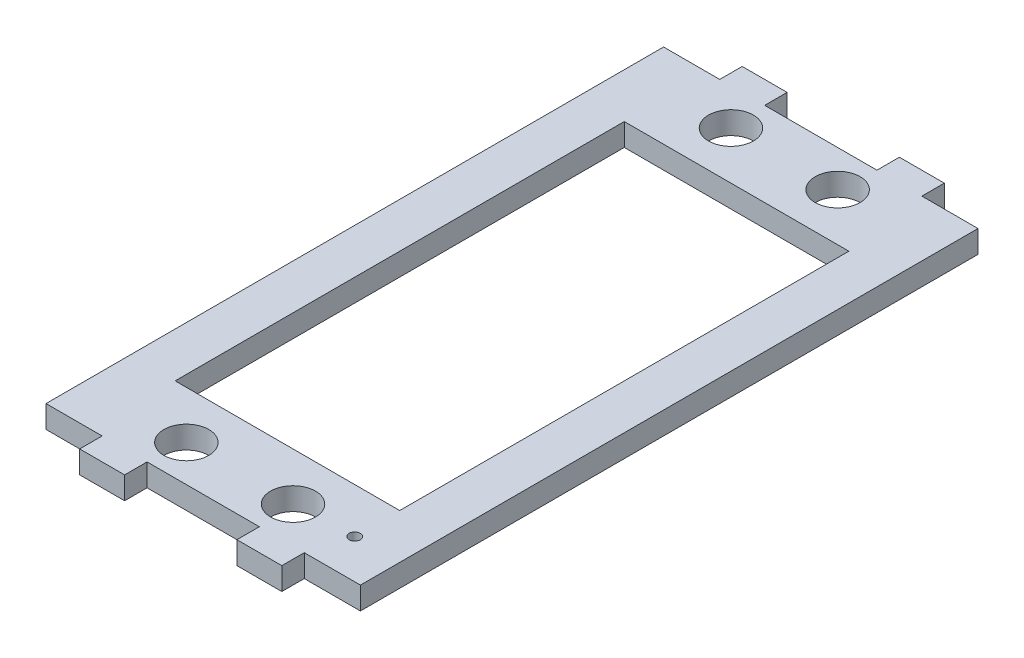
SolidWorks part; units mm, degrees
ref_plane "Front Plane" through (0, 0, 0) normal (0, 0, 1) x (1, 0, 0)
ref_plane "Top Plane" through (0, 0, 0) normal (0, 1, 0) x (1, 0, 0)
ref_plane "Right Plane" through (0, 0, 0) normal (1, 0, 0) x (0, 0, -1)
sketch "Sketch1" plane through (0, 0, 0) normal (0, 1, 0) x (1, 0, 0)
  line L0 (0, 27.2) -> (0, -27.2) construction
  line L1 (-10, -20) -> (10, -20)
  line L2 (-10, -20) -> (-10, 20)
  line L3 (-10, 20) -> (10, 20)
  line L4 (10, -20) -> (10, 20)
  line L5 (-10, -20) -> (10, 20) construction
  line L6 (-10, 20) -> (10, -20) construction
  line L7 (-14, -27.5) -> (-9, -27.5)
  line L8 (-14, -14.5) -> (-14, 14.5)
  line L9 (-14, 27.5) -> (-9, 27.5)
  line L10 (14, -27.5) -> (14, 27.5)
  line L11 (-14, -27.5) -> (14, 27.5) construction
  line L12 (-14, 27.5) -> (14, -27.5) construction
  line L18 (5, 27.5) -> (5, 29.5)
  line L19 (5, 29.5) -> (9, 29.5)
  line L20 (9, 27.5) -> (9, 29.5)
  line L21 (-14, 0) -> (14, 0) construction
  line L22 (9, 27.5) -> (14, 27.5)
  line L23 (-9, 27.5) -> (-9, 29.5)
  line L24 (-5, 29.5) -> (-9, 29.5)
  line L25 (-5, 27.5) -> (-5, 29.5)
  line L26 (-9, -27.5) -> (-9, -29.5)
  line L27 (-5, -29.5) -> (-9, -29.5)
  line L28 (-5, -27.5) -> (-5, -29.5)
  line L29 (9, -27.5) -> (9, -29.5)
  line L30 (5, -27.5) -> (5, -29.5)
  line L31 (5, -29.5) -> (9, -29.5)
  line L32 (-5, -27.5) -> (5, -27.5)
  line L33 (9, -27.5) -> (14, -27.5)
  line L34 (-5, 27.5) -> (5, 27.5)
  line L87 (-14, 14.5) -> (-14, 27.5)
  line L88 (-14, -14.5) -> (-14, -27.5)
  point P0 (0, 0)
  point P6 (0, 0)
  dimension "D1" = 20
  dimension "D2" = 40
  dimension "D3" = 55
  dimension "D4" = 4
  dimension "D5" = 2
  dimension "D6" = 4
  dimension "D7" = 5
extrude "Boss-Extrude1" add sketch "Sketch1" along normal blind 2
sketch "Sketch2" plane through (0, 2, 0) normal (0, 1, 0) x (1, 0, 0)
  line L0 (0, -20) -> (0, 20) construction
  line L1 (-10, -20) -> (10, -20) construction
  line L2 (10, 20) -> (-10, 20) construction
  line L3 (10, 0) -> (0, 0) construction
  line L4 (10, -20) -> (10, 20) construction
  circle A0 centre (4.75, 24.25) radius 2
  circle A1 centre (-4.75, 24.25) radius 2
  circle A2 centre (4.75, -24.25) radius 2
  circle A3 centre (-4.75, -24.25) radius 2
  circle A4 centre (10, -24.01) radius 0.5
  dimension "D1" = 4
  dimension "D3" = 4.25
  dimension "D4" = 4
  dimension "D7" = 1
  dimension "D2" = 4.75
  dimension "D5" = 4.75
  dimension "D6" = 4.25
extrude "Cut-Extrude1" cut sketch "Sketch2" against normal blind 2
